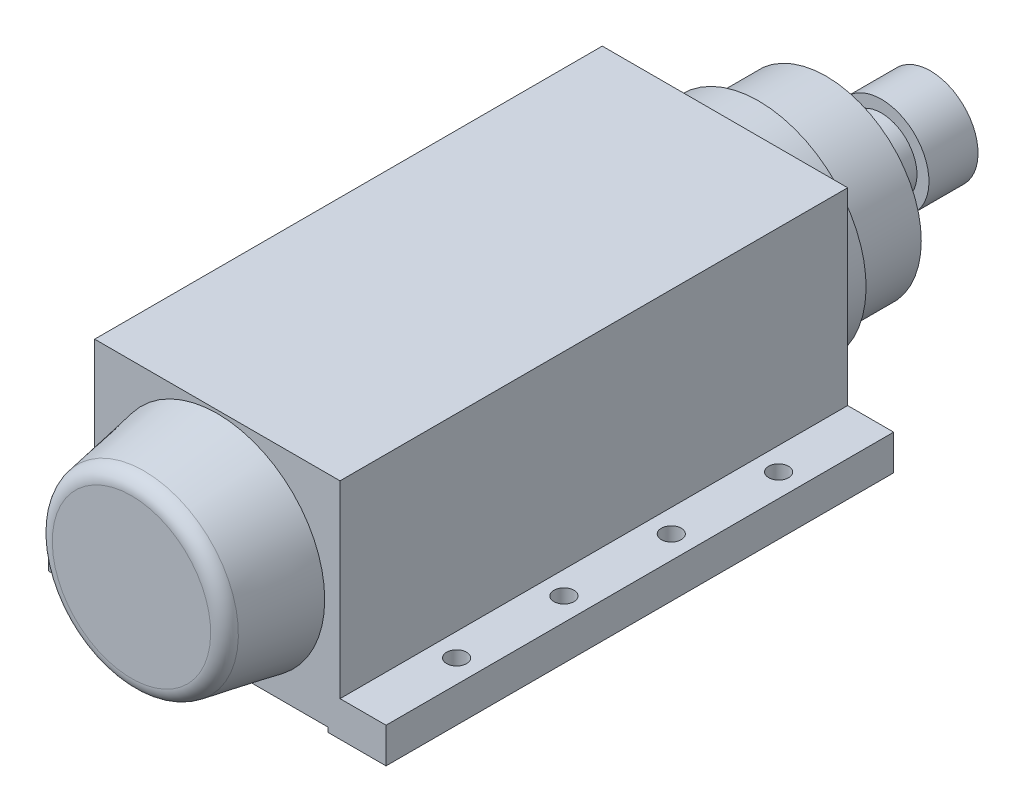
SolidWorks part; units mm, degrees
ref_plane "Ebene vorne" through (0, 0, 0) normal (0, 0, 1) x (1, 0, 0)
ref_plane "Ebene oben" through (0, 0, 0) normal (0, 1, 0) x (1, 0, 0)
ref_plane "Ebene rechts" through (0, 0, 0) normal (1, 0, 0) x (0, 0, -1)
sketch "Skizze1" plane through (0, 0, 0) normal (0, 0, 1) x (1, 0, 0)
  line L0 (0, 0) -> (0, 83.7667) construction
  line L1 (-36, 1.5) -> (36, 1.5)
  line L2 (36, 1.5) -> (36, 0)
  line L3 (36, 0) -> (55, 0)
  line L4 (55, 0) -> (55, 11.5)
  line L5 (55, 11.5) -> (40, 11.5)
  line L6 (40, 11.5) -> (40, 73)
  line L7 (40, 73) -> (-40, 73)
  line L8 (-40, 11.5) -> (-40, 73)
  line L9 (-55, 11.5) -> (-40, 11.5)
  line L10 (-55, 0) -> (-55, 11.5)
  line L11 (-36, 0) -> (-55, 0)
  line L12 (-36, 1.5) -> (-36, 0)
  point P3 (0, 83.7667)
  point P12 (0, 73)
  point P17 (0, 1.5)
  dimension "D1" = 11.5
  dimension "D2" = 1.5
  dimension "D3" = 72
  dimension "D4" = 110
  dimension "D5" = 80
  dimension "D6" = 73
extrude "Aufsatz-Linear austragen1" add sketch "Skizze1" along normal blind 165.5
sketch "Skizze2" plane through (0, 0, 0) normal (1, 0, 0) x (0, 0, -1)
  line L0 (51.7309, 37) -> (-231.4602, 37) construction
  line L1 (-165.5, 72) -> (-189.379, 67.7359)
  line L2 (-165.5, 0) -> (0, 0) construction
  line L3 (-165.5, 11.5) -> (-165.5, 73) construction
  line L4 (-193.5, 62.8138) -> (-193.5, 37)
  line L5 (-193.5, 37) -> (-165.5, 37)
  line L6 (-165.5, 37) -> (-165.5, 72)
  line L7 (0, 72) -> (11, 72)
  line L8 (0, 11.5) -> (0, 73) construction
  line L9 (11, 72) -> (11, 68)
  line L10 (11, 68) -> (33, 68)
  line L11 (33, 68) -> (33, 62)
  line L12 (33, 62) -> (35, 62)
  line L13 (35, 62) -> (36, 61.4226)
  line L14 (36, 61.4226) -> (36, 48.6)
  line L15 (36, 48.6) -> (51, 48.6)
  line L16 (51, 48.6) -> (51, 52.5)
  line L17 (51, 52.5) -> (67, 52.5)
  line L18 (67, 52.5) -> (67, 37)
  line L19 (67, 37) -> (0, 37)
  line L20 (0, 37) -> (0, 72)
  arc A0 (-189.379, 67.7359) -> (-193.5, 62.8138) centre (-188.5, 62.8138) ccw
  point P12 (-193.5, 67)
  point P21 (0, 0)
  dimension "D5" = 5
  dimension "D1" = 37
  dimension "D2" = 70
  dimension "D3" = 28
  dimension "D4" = 60
  dimension "D6" = 70
  dimension "D7" = 62
  dimension "D8" = 50
  dimension "D9" = 23.2
  dimension "D10" = 31
  dimension "D11" = 11
  dimension "D12" = 33
  dimension "D13" = 2
  dimension "D14" = 30
  dimension "D15" = 15
  dimension "D16" = 16
  dimension "D17" = 34
revolve "Rotation1" add sketch "Skizze2" angle 360 about L0
sketch "Skizze3" plane through (0, 0, 0) normal (0, -1, 0) x (1, 0, 0)
  line L0 (0, 0) -> (0, 200.4068) construction
  line L3 (47.5, 0) -> (47.5, 165.5) construction
  line L4 (36, 0) -> (55, 0) construction
  line L5 (36, 165.5) -> (55, 165.5) construction
  circle A0 centre (47.5, 30) radius 3.25
  circle A1 centre (47.5, 65) radius 3.25
  circle A2 centre (47.5, 100) radius 3.25
  circle A3 centre (47.5, 135) radius 3.25
  circle A4 centre (-47.5, 30) radius 3.25
  circle A5 centre (-47.5, 65) radius 3.25
  circle A6 centre (-47.5, 100) radius 3.25
  circle A7 centre (-47.5, 135) radius 3.25
  dimension "D6" = 6.5
  dimension "D1" = 47.5
  dimension "D2" = 30
  dimension "D3" = 35
  dimension "D4" = 35
  dimension "D5" = 35
extrude "Schnitt-Linear austragen1" cut sketch "Skizze3" against normal blind 20
